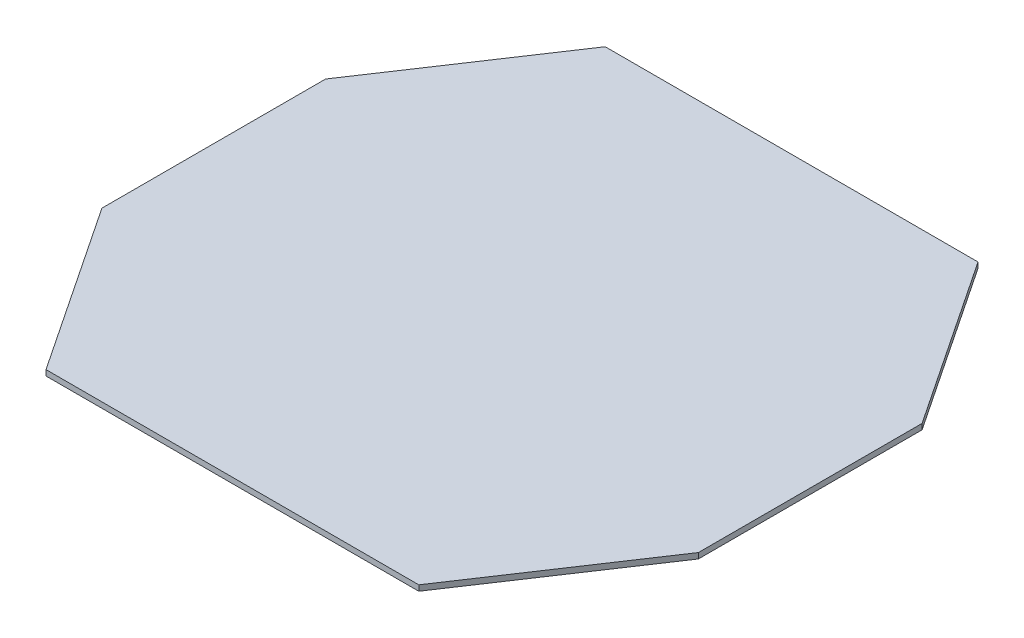
SolidWorks part; units mm, degrees
ref_plane "Front Plane" through (0, 0, 0) normal (0, 0, 1) x (1, 0, 0)
ref_plane "Top Plane" through (0, 0, 0) normal (0, 1, 0) x (1, 0, 0)
ref_plane "Right Plane" through (0, 0, 0) normal (1, 0, 0) x (0, 0, -1)
sketch "Sketch2" plane through (0, 0, 0) normal (0, 1, 0) x (1, 0, 0)
  line L0 (-100, 150) -> (100, 150)
  line L1 (100, 150) -> (160, 60)
  line L2 (160, 60) -> (160, -60)
  line L3 (160, -60) -> (100, -150)
  line L4 (100, -150) -> (-100, -150)
  line L5 (-100, -150) -> (-160, -60)
  line L6 (-160, -60) -> (-160, 60)
  line L7 (-160, 60) -> (-100, 150)
  point P8 (0, 0)
  point P10 (0, 0)
  point P11 (0, 0)
  dimension "D1" = 300
  dimension "D2" = 320
  dimension "D3" = 160
  dimension "D4" = 150
  dimension "D5" = 200
  dimension "D6" = 200
  dimension "D7" = 60
  dimension "D8" = 60
  dimension "D9" = 90
  dimension "D10" = 120
  dimension "D11" = 120
  dimension "D12" = 90
extrude "Boss-Extrude1" add sketch "Sketch2" along normal blind 3
